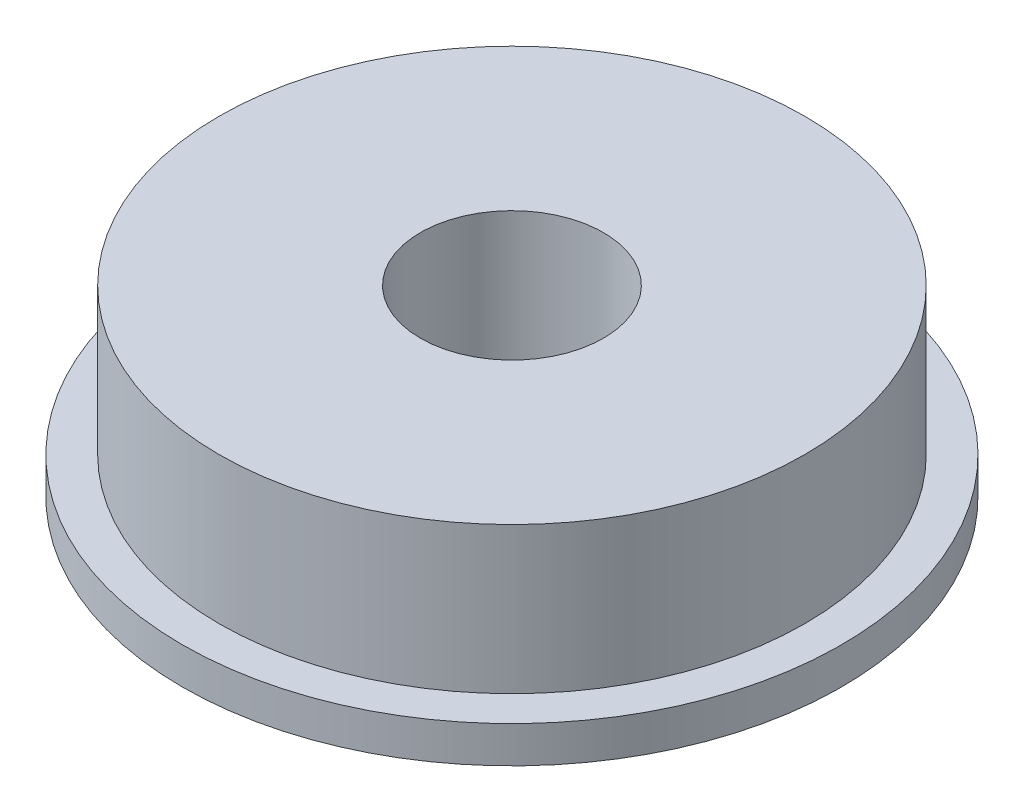
SolidWorks part; units mm, degrees
material "1060 Сплав"
ref_plane "Front" through (0, 0, 0) normal (0, 0, 1) x (1, 0, 0)
ref_plane "Top" through (0, 0, 0) normal (0, 1, 0) x (1, 0, 0)
ref_plane "Right" through (0, 0, 0) normal (1, 0, 0) x (0, 0, -1)
sketch "Эскиз1" plane through (0, 0, 0) normal (0, 1, 0) x (1, 0, 0)
  circle A0 centre (0, 0) radius 2.5
  circle A1 centre (0, 0) radius 9
extrude "Бобышка-Вытянуть1" add sketch "Эскиз1" along normal blind 1
sketch "Эскиз2" plane through (0, 1, 0) normal (0, 1, 0) x (1, 0, 0)
  circle A0 centre (0, 0) radius 2.5
  circle A1 centre (0, 0) radius 8
extrude "Бобышка-Вытянуть2" add sketch "Эскиз2" along normal blind 4
